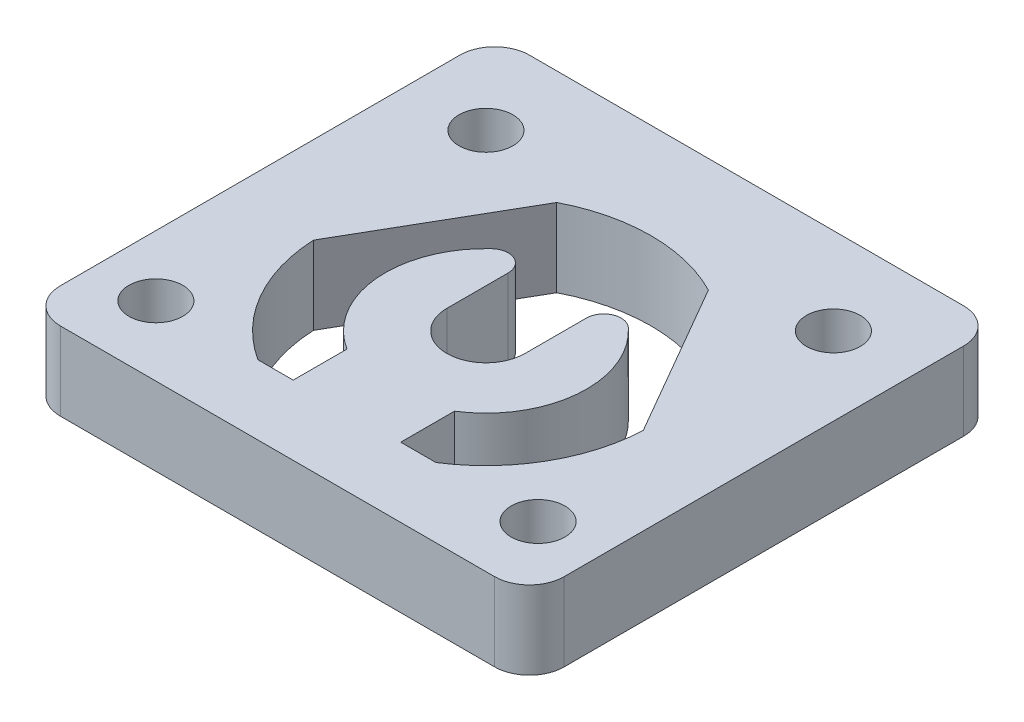
SolidWorks part; units mm, degrees
ref_plane "Front Plane" through (0, 0, 0) normal (0, 0, 1) x (1, 0, 0)
ref_plane "Top Plane" through (0, 0, 0) normal (0, 1, 0) x (1, 0, 0)
ref_plane "Right Plane" through (0, 0, 0) normal (1, 0, 0) x (0, 0, -1)
sketch "Sketch3" plane through (0, 0, 0) normal (0, 1, 0) x (1, 0, 0)
  line L0 (0, 0) -> (7.5782, 0) construction
  line L1 (0, 0) -> (0, -13.6906) construction
  line L2 (3.0948, -4.9054) -> (3.0948, -8)
  line L3 (-4.3665, 8.4371) -> (-9.4899, -0.4371)
  line L4 (-3.0948, -4.9054) -> (-3.0948, -8)
  line L5 (-5.1235, -8) -> (-3.0948, -8)
  line L6 (0, 0) -> (5.826, 3.3636) construction
  line L7 (4.3665, 8.4371) -> (9.4899, -0.4371)
  line L8 (-5.1235, -8) -> (5.1235, -8) construction
  line L9 (5.1235, -8) -> (3.0948, -8)
  line L10 (-14.5, -10) -> (-14.5, 13)
  line L11 (-12.5, -12) -> (12.5, -12)
  line L13 (-12.5, 15) -> (12.5, 15)
  line L14 (14.5, -10) -> (14.5, 13)
  line L15 (-2.25, 3.5324) -> (-2.25, 0)
  line L16 (2.25, 3.5324) -> (2.25, 0)
  arc A0 (3.0948, -4.9054) -> (3.9271, 4.2683) centre (0, 0) ccw
  circle A1 centre (0, 0) radius 9.5 construction
  arc A2 (4.3665, 8.4371) -> (-4.3665, 8.4371) centre (0, 0) ccw
  arc A3 (9.4899, -0.4371) -> (5.1235, -8) centre (0, 0) cw
  arc A4 (-9.4899, -0.4371) -> (-5.1235, -8) centre (0, 0) ccw
  circle A5 centre (10, 10) radius 1.55
  circle A6 centre (11, -8) radius 1.55
  circle A7 centre (-11, -8) radius 1.55
  circle A8 centre (-10, 10) radius 1.55
  arc A9 (12.5, 15) -> (14.5, 13) centre (12.5, 13) cw
  arc A10 (12.5, -12) -> (14.5, -10) centre (12.5, -10) ccw
  arc A11 (-14.5, -10) -> (-12.5, -12) centre (-12.5, -10) ccw
  arc A12 (-14.5, 13) -> (-12.5, 15) centre (-12.5, 13) cw
  arc A13 (-2.25, 0) -> (2.25, 0) centre (0, 0) ccw
  arc A14 (-3.9271, 4.2683) -> (-3.0948, -4.9054) centre (0, 0) ccw
  arc A15 (2.25, 3.5324) -> (3.9271, 4.2683) centre (3.25, 3.5324) cw
  arc A16 (-2.25, 3.5324) -> (-3.9271, 4.2683) centre (-3.25, 3.5324) ccw
  point P18 (0, -12)
  point P33 (0, 15)
  point P35 (14.5, 15)
  point P38 (14.5, -12)
  point P41 (-14.5, -12)
  point P44 (-14.5, 15)
  point P51 (2.25, 5.3458)
  point P54 (-2.25, 5.3458)
  dimension "D1" = 11.6
  dimension "D5" = 19
  dimension "D3" = 18
  dimension "D4" = 10
  dimension "D8" = 10
  dimension "D9" = 11
  dimension "D10" = 3.1
  dimension "D12" = 3.5
  dimension "D11" = 4
  dimension "D14" = 5
  dimension "D15" = 2
  dimension "D16" = 4.5
  dimension "D17" = 1
  dimension "D2" = 60
  dimension "D6" = 8
  dimension "D7" = 8
  dimension "D13" = 3.0946
extrude "Boss-Extrude1" add sketch "Sketch3" along normal blind 4.5
